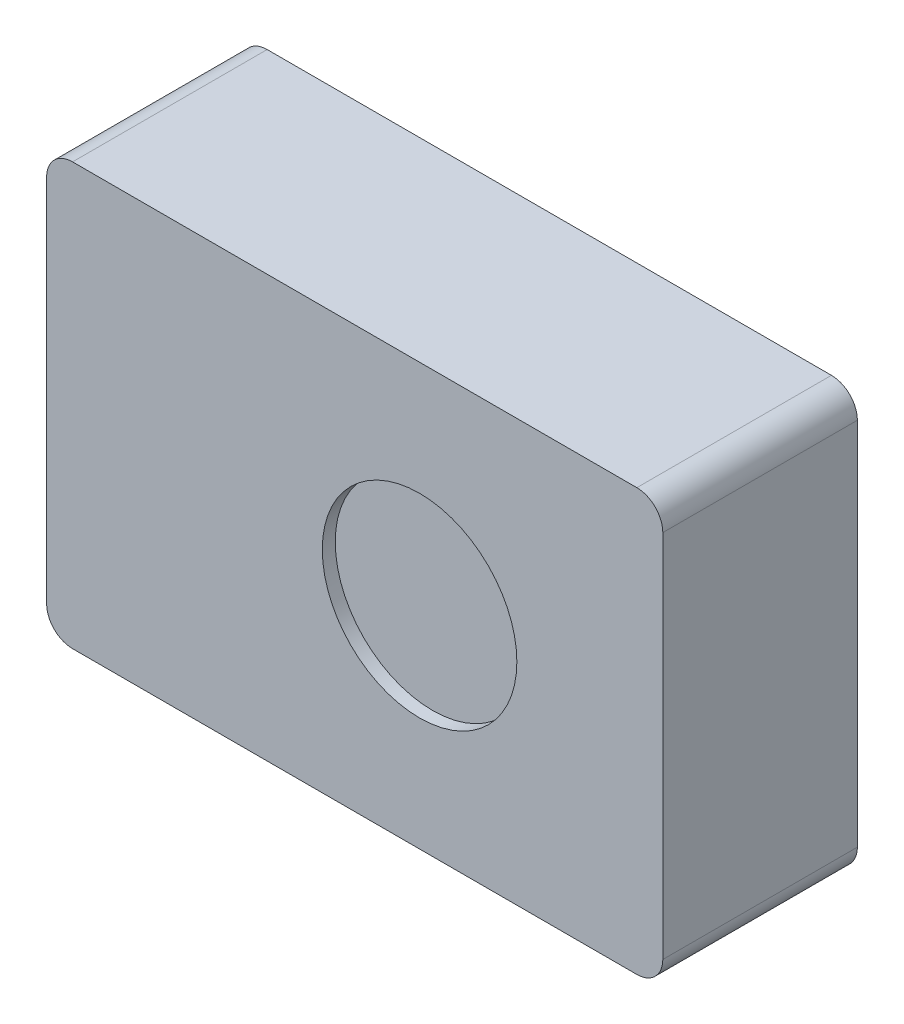
SolidWorks part; units mm, degrees
ref_plane "Alzado" through (0, 0, 0) normal (0, 0, 1) x (1, 0, 0)
ref_plane "Planta" through (0, 0, 0) normal (0, 1, 0) x (1, 0, 0)
ref_plane "Vista lateral" through (0, 0, 0) normal (1, 0, 0) x (0, 0, -1)
sketch "Croquis1" plane through (0, 0, 0) normal (0, 0, 1) x (1, 0, 0)
  line L0 (-43.5, -32.5) -> (43.5, -32.5)
  line L1 (47.5, -28.5) -> (47.5, 28.5)
  line L2 (43.5, 32.5) -> (-43.5, 32.5)
  line L3 (-47.5, 28.5) -> (-47.5, -28.5)
  arc A0 (43.5, -32.5) -> (47.5, -28.5) centre (43.5, -28.5) ccw
  arc A1 (47.5, 28.5) -> (43.5, 32.5) centre (43.5, 28.5) ccw
  arc A2 (-43.5, 32.5) -> (-47.5, 28.5) centre (-43.5, 28.5) ccw
  arc A3 (-47.5, -28.5) -> (-43.5, -32.5) centre (-43.5, -28.5) ccw
  dimension "D1" = 4
  dimension "D2" = 4
  dimension "D3" = 4
  dimension "D4" = 4
  dimension "D5" = 43.5
  dimension "D6" = 32.5
  dimension "D7" = 43.5
  dimension "D8" = 32.5
  dimension "D9" = 47.5
  dimension "D10" = 28.5
  dimension "D11" = 47.5
  dimension "D12" = 28.5
  dimension "D13" = 43.5
  dimension "D14" = 32.5
  dimension "D15" = 43.5
  dimension "D16" = 32.5
  dimension "D17" = 47.5
  dimension "D18" = 28.5
  dimension "D19" = 47.5
  dimension "D20" = 28.5
extrude "Envolvente_95x65x30" add sketch "Croquis1" along normal blind 30
sketch "Croquis2" plane through (0, 0, 0) normal (0, 0, 1) x (1, 0, 0)
  circle A0 centre (10, 0) radius 15
  dimension "D1" = 30
  dimension "D2" = 10
extrude "Ventilador" cut sketch "Croquis2" along normal blind 2 from offset 28
